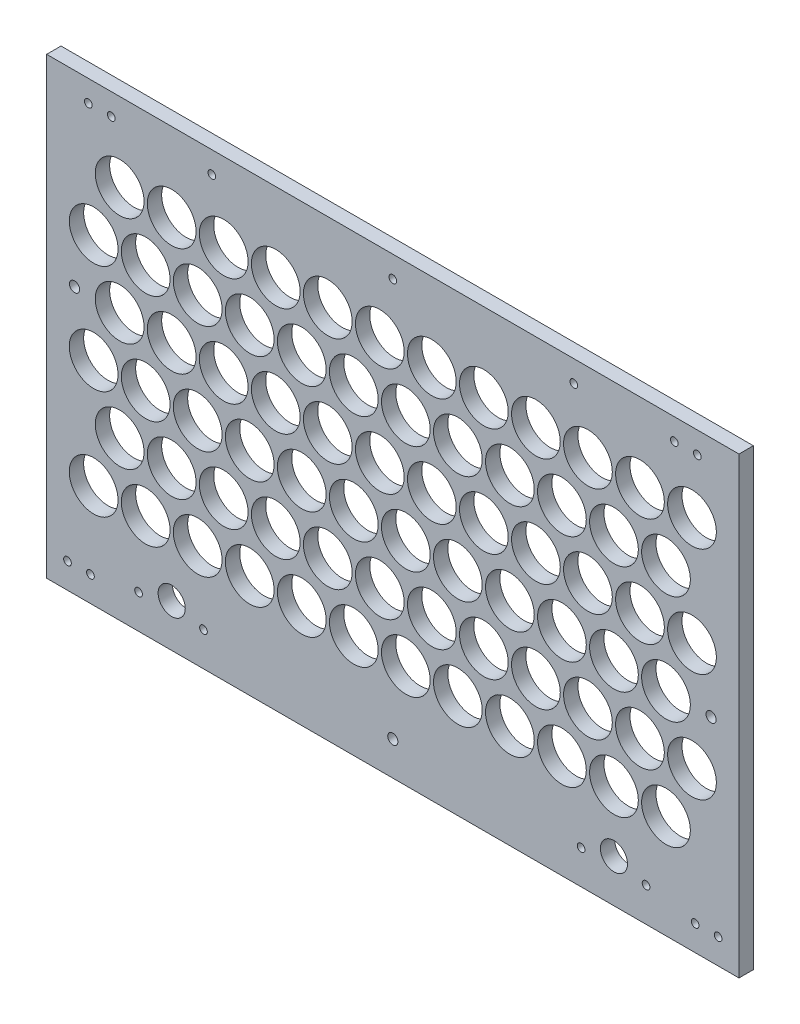
SolidWorks part; units mm, degrees
material "ABS"
ref_plane "X-Y Datum" through (0, 0, 0) normal (0, 0, 1) x (1, 0, 0)
ref_plane "X-Z Datum" through (0, 0, 0) normal (0, 1, 0) x (1, 0, 0)
ref_plane "Y-Z Datum" through (0, 0, 0) normal (1, 0, 0) x (0, 0, -1)
sketch "Sketch1" plane through (0, 0, 0) normal (0, 0, 1) x (1, 0, 0)
  line L1 (-143.025, 70.775) -> (143.025, 70.775)
  line L2 (-143.025, 70.775) -> (-143.025, -70.775)
  line L3 (-143.025, -70.775) -> (143.025, -70.775)
  line L4 (143.025, 70.775) -> (143.025, -70.775)
  line L5 (-143.025, 70.775) -> (143.025, -70.775) construction
  line L6 (-143.025, -70.775) -> (143.025, 70.775) construction
  line L13 (-153.025, -105.775) -> (153.025, -105.775)
  line L14 (-153.025, 91.65) -> (153.025, 91.65)
  line L15 (-153.025, 91.65) -> (-153.025, -105.775)
  line L16 (153.025, 91.65) -> (153.025, -105.775)
  line L17 (153.025, 70.775) -> (153.025, -70.775) construction
  line L18 (-143.025, 91.65) -> (143.025, 91.65) construction
  line L19 (-143.025, -105.775) -> (143.025, -105.775) construction
  line L20 (-153.025, 70.775) -> (-153.025, -70.775) construction
  line L21 (-132.25, -60) -> (-109.25, -60) construction
  circle A0 centre (-132.25, -60) radius 10.775
  circle A1 centre (-109.25, -60) radius 10.775 construction
  circle A2 centre (-120.75, -36) radius 10.775
  point P0 (0, 0)
  point P16 (-120.75, -60)
  dimension "D1" = 21.55
  dimension "D2" = 23
  dimension "D3" = 24
  dimension "D5" = 141.55
  dimension "D6" = 286.05
  dimension "D7" = 35
  dimension "D8" = 20.875
  dimension "D9" = 10
  dimension "D10" = 10
extrude "Boss-Extrude1" add sketch "Sketch1" along normal blind 6.35
sketch "Sketch3" plane through (0, 0, 6.35) normal (0, 0, 1) x (1, 0, 0)
  line L4 (143.025, 70.775) -> (-143.025, 70.775)
  line L5 (143.025, -70.775) -> (143.025, 70.775)
  line L6 (-143.025, -70.775) -> (143.025, -70.775)
  line L7 (-143.025, 70.775) -> (-143.025, -70.775)
  line L8 (143.025, 70.775) -> (-143.025, 70.775)
  line L9 (143.025, -70.775) -> (143.025, 70.775)
  line L10 (-143.025, -70.775) -> (143.025, -70.775)
  line L11 (-143.025, 70.775) -> (-143.025, -70.775)
  circle A1 centre (-120.75, -36) radius 10.775
  circle A2 centre (-120.75, -36) radius 10.775
  circle A3 centre (-132.25, -60) radius 10.775
  circle A4 centre (-132.25, -60) radius 10.775
  dimension "D1" = 0
  dimension "D2" = 0
  dimension "D3" = 0
extrude "Cut-Extrude1" cut sketch "Sketch3" against normal through all contours A4
sketch "Sketch4" plane through (0, 0, 6.35) normal (0, 0, 1) x (1, 0, 0)
  line L4 (143.025, 70.775) -> (-143.025, 70.775)
  line L5 (143.025, -70.775) -> (143.025, 70.775)
  line L6 (-143.025, -70.775) -> (143.025, -70.775)
  line L7 (-143.025, 70.775) -> (-143.025, -70.775)
  line L8 (143.025, 70.775) -> (-143.025, 70.775)
  line L9 (143.025, -70.775) -> (143.025, 70.775)
  line L10 (-143.025, -70.775) -> (143.025, -70.775)
  line L11 (-143.025, 70.775) -> (-143.025, -70.775)
  circle A1 centre (-120.75, -36) radius 10.775
  circle A2 centre (-120.75, -36) radius 10.775
  circle A3 centre (-132.25, -60) radius 10.775
  circle A4 centre (-132.25, -60) radius 10.775
  dimension "D1" = 0
  dimension "D2" = 0
  dimension "D3" = 0
extrude "Cut-Extrude2" cut sketch "Sketch4" against normal through all contours A2
pattern_linear "LPattern1" count 12 spacing 23 along (1, 0, 0) of "Cut-Extrude1", "Cut-Extrude2"
pattern_linear "LPattern2" count 3 spacing 48 along (0, 1, 0) of "LPattern1", "Cut-Extrude1", "Cut-Extrude2"
sketch "Sketch5" plane through (0, 0, 0) normal (0, 0, -1) x (-1, 0, 0)
sketch "Sketch13" plane through (0, 91.65, 0) normal (0, 1, 0) x (1, 0, 0)
  line L4 (153.025, 0) -> (-153.025, 0)
  line L5 (-153.025, 0) -> (-153.025, -6.35)
  line L6 (-153.025, -6.35) -> (153.025, -6.35)
  line L7 (153.025, -6.35) -> (153.025, 0)
  line L8 (153.025, 0) -> (-153.025, 0)
  line L9 (-153.025, 0) -> (-153.025, -6.35)
  line L10 (-153.025, -6.35) -> (153.025, -6.35)
  line L11 (153.025, -6.35) -> (153.025, 0)
  dimension "D1" = 0
extrude "Boss-Extrude2" add sketch "Sketch13" along normal blind 3.175
sketch "Sketch14" plane through (0, 0, 0) normal (0, 0, -1) x (-1, 0, 0)
  circle A0 centre (-97.75, -86.775) radius 6
extrude "Cut-Extrude3" cut sketch "Sketch14" against normal through all
mirror "Mirror1" about plane through (0, 0, 0) normal (1, 0, 0) of "Cut-Extrude3"
sketch "Sketch15" plane through (0, 0, 0) normal (0, 0, -1) x (-1, 0, 0)
  point P0 (-111.94, -90.775)
  point P1 (-83.25, -90.775)
  point P3 (83.712, -90.775)
  point P7 (134.61, 85.3)
  point P9 (124.45, 85.3)
  point P11 (80, 85.3)
  point P13 (0, 85.3)
  point P15 (-80, 85.3)
  point P17 (-124.45, 85.3)
  point P19 (-134.61, 85.3)
  point P25 (143.8175, -94.6)
  point P27 (133.6575, -94.6)
  point P29 (-133.6575, -94.6)
  point P31 (-143.8175, -94.6)
  point P41 (112.402, -90.775)
hole_wizard "M3 Clearance Hole1" positions "Sketch15" profile "Sketch16" hole size "M3" standard "ANSI Metric" end condition through all
sketch "Sketch16" plane through (111.94, -90.775, 0) normal (1, 0, 0) x (0, 1, 0)
  line L0 (0, 0) -> (0, 6.35)
  line L1 (0, 6.35) -> (1.7, 6.35)
  line L2 (1.7, 6.35) -> (1.7, 0)
  line L5 (1.7, 0) -> (0, 0)
  line L11 (0, -6.35) -> (0, 107.95) construction
  dimension "Thru Hole Dia." = 3.4
  dimension "Thru Hole Depth" = 6.35
sketch "Sketch17" plane through (0, 0, 0) normal (0, 0, -1) x (-1, 0, 0)
  line L0 (0, -105.775) -> (0, -77.9164) construction
  line L1 (153.025, -105.775) -> (-153.025, -105.775) construction
  circle A0 centre (0, -90.775) radius 2.25
  circle A1 centre (140.6875, 12) radius 2.25
  circle A2 centre (-140.6875, -12) radius 2.25
  point P0 (-140.6875, -12)
  point P1 (140.6875, 12)
  point P9 (0, -90.775)
  point P11 (83.712, -90.775)
  dimension "D1" = 4.5
extrude "Cut-Extrude4" cut sketch "Sketch17" against normal through all
